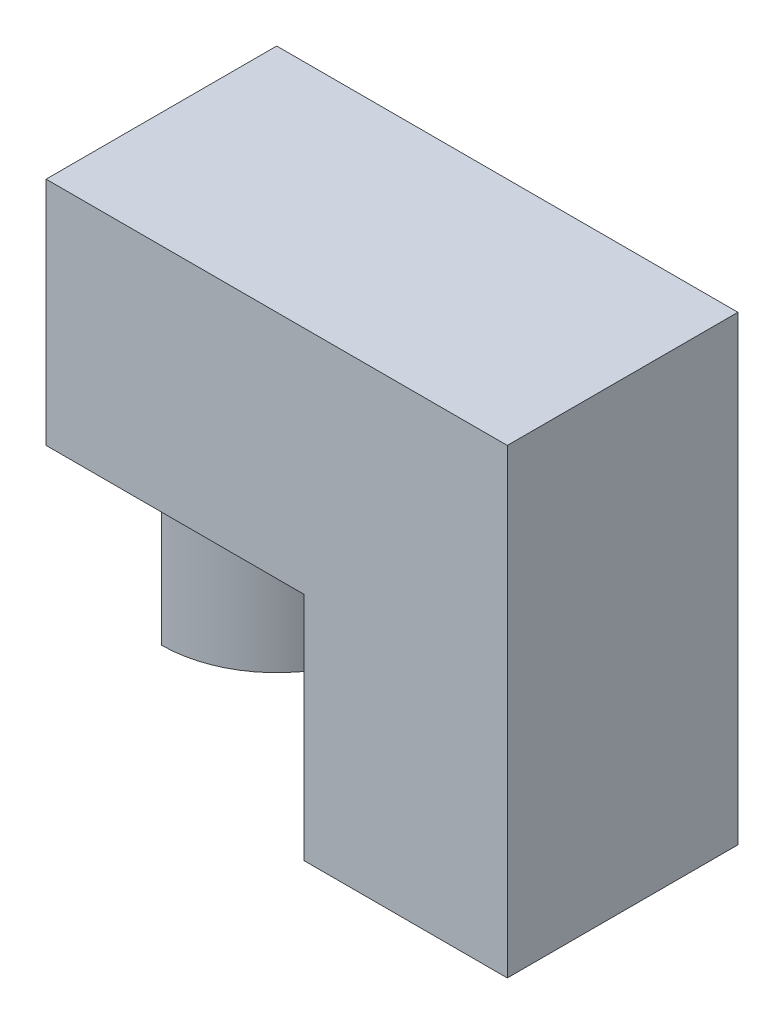
SolidWorks part; units mm, degrees
ref_plane "前视基准面" through (0, 0, 0) normal (0, 0, 1) x (1, 0, 0)
ref_plane "上视基准面" through (0, 0, 0) normal (0, 1, 0) x (1, 0, 0)
ref_plane "右视基准面" through (0, 0, 0) normal (1, 0, 0) x (0, 0, -1)
other "Configuration Table"
sketch "草图1" plane through (0, 0, 0) normal (0, 0, 1) x (1, 0, 0)
  line L1 (0, 0) -> (20, 0)
  line L2 (0, 0) -> (0, 20)
  line L3 (0, 20) -> (20, 20)
  line L4 (20, 0) -> (20, 20)
extrude "BaseBox" add sketch "草图1" along normal blind 10
sketch "草图2" plane through (0, 0, 0) normal (0, 0, 1) x (1, 0, 0)
  line L0 (0, 0) -> (0, 20) construction
  line L2 (5, 0) -> (15, 0)
  line L3 (5, 0) -> (5, 10)
  line L4 (5, 10) -> (15, 10)
  line L5 (15, 0) -> (15, 10)
revolve "RevolveCut360" cut sketch "草图2" angle 360 about L0
